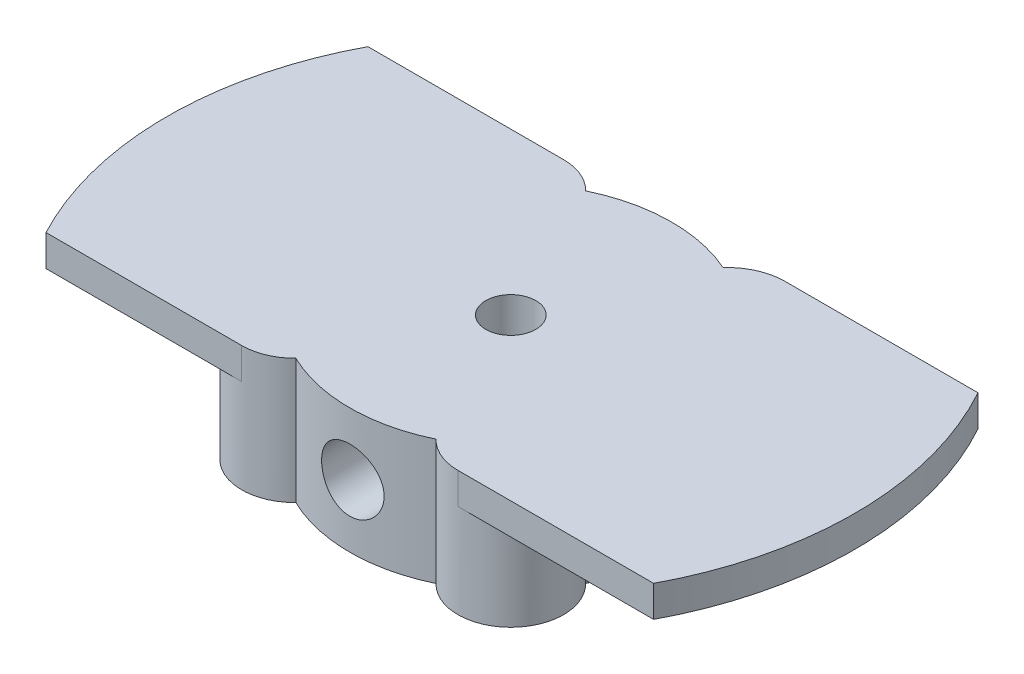
SolidWorks part; units mm, degrees
ref_plane "Front Plane" through (0, 0, 0) normal (0, 0, 1) x (1, 0, 0)
ref_plane "Top Plane" through (0, 0, 0) normal (0, 1, 0) x (1, 0, 0)
ref_plane "Right Plane" through (0, 0, 0) normal (1, 0, 0) x (0, 0, -1)
sketch "Sketch1" plane through (0, 0, 0) normal (0, 1, 0) x (1, 0, 0)
  line L0 (-10.3, 0) -> (-10.3, -6.915) construction
  line L1 (-6.915, -6.915) -> (6.915, -6.915) construction
  line L2 (-6.915, -6.915) -> (-6.915, 6.915) construction
  line L3 (-6.915, 6.915) -> (6.915, 6.915) construction
  line L4 (6.915, -6.915) -> (6.915, 6.915) construction
  line L5 (-6.915, -6.915) -> (6.915, 6.915) construction
  line L6 (-6.915, 6.915) -> (6.915, -6.915) construction
  arc A5 (-9.272, -4.4855) -> (-4.4855, -9.272) centre (-6.915, -6.915) ccw
  arc A6 (4.4855, -9.272) -> (9.272, -4.4855) centre (6.915, -6.915) ccw
  arc A7 (9.4218, 4.1617) -> (4.1617, 9.4218) centre (6.915, 6.915) ccw
  arc A8 (-4.4855, 9.272) -> (-9.272, 4.4855) centre (-6.915, 6.915) ccw
  arc A9 (-4.4855, -9.272) -> (4.4855, -9.272) centre (0, 0) ccw
  arc A10 (9.272, -4.4855) -> (9.4218, 4.1617) centre (0, 0) ccw
  arc A11 (4.1617, 9.4218) -> (-4.4855, 9.272) centre (0, 0) ccw
  arc A12 (-9.272, 4.4855) -> (-9.272, -4.4855) centre (0, 0) ccw
  circle A13 centre (0, 0) radius 1.6
  dimension "D1" = 10.3
  dimension "D3" = 3.2
  dimension "D2" = 13.83
extrude "Boss-Extrude1" add sketch "Sketch1" along normal blind 8
sketch "Sketch3" plane through (0, 0, 0) normal (0, 0, 1) x (1, 0, 0)
  line L0 (0, 0) -> (0, 4) construction
  line L1 (-4.4855, 0) -> (4.4855, 0) construction
  circle A0 centre (0, 4) radius 2
  dimension "D1" = 4
  dimension "D2" = 4
extrude "Cut-Extrude1" cut sketch "Sketch3" along normal blind 14.5
sketch "Sketch4" plane through (0, 8, 0) normal (0, 1, 0) x (1, 0, 0)
  line L0 (-19.4399, 10.3) -> (-6.915, 10.3)
  line L1 (19.2567, 10.6385) -> (6.915, 10.6385)
  line L2 (-19.4399, -10.3) -> (-6.915, -10.3)
  line L3 (19.4399, -10.3) -> (6.915, -10.3)
  arc A0 (-19.4399, 10.3) -> (-19.4399, -10.3) centre (0, 0) ccw
  arc A1 (-4.4855, 9.272) -> (-9.272, 4.4855) centre (-6.915, 6.915) ccw construction
  arc A2 (9.4218, 4.1617) -> (4.1617, 9.4218) centre (6.915, 6.915) ccw construction
  arc A3 (-9.272, -4.4855) -> (-4.4855, -9.272) centre (-6.915, -6.915) ccw construction
  arc A4 (4.4855, -9.272) -> (9.272, -4.4855) centre (6.915, -6.915) ccw construction
  arc A5 (19.4399, -10.3) -> (19.2567, 10.6385) centre (0, 0) ccw
  arc A6 (-6.915, 10.3) -> (-9.272, 4.4855) centre (-6.915, 6.915) ccw
  arc A7 (-9.272, 4.4855) -> (-9.272, -4.4855) centre (0, 0) ccw
  arc A8 (-6.915, -10.3) -> (-9.272, -4.4855) centre (-6.915, -6.915) cw
  arc A9 (6.915, -10.3) -> (9.272, -4.4855) centre (6.915, -6.915) ccw
  arc A10 (9.4218, 4.1617) -> (9.272, -4.4855) centre (0, 0) cw
  arc A11 (6.915, 10.6385) -> (9.4218, 4.1617) centre (6.915, 6.915) cw
  dimension "D1" = 44
extrude "Boss-Extrude3" add sketch "Sketch4" against normal blind 2
sketch "Sketch5" plane through (0, 0, 0) normal (0, -1, 0) x (1, 0, 0)
  circle A0 centre (-6.915, 6.915) radius 2.25
  circle A1 centre (6.915, 6.915) radius 2.25
  circle A2 centre (6.915, -6.915) radius 2.25
  circle A3 centre (-6.915, -6.915) radius 2.25
  dimension "D1" = 4.5
extrude "Cut-Extrude2" cut sketch "Sketch5" against normal blind 6.3
